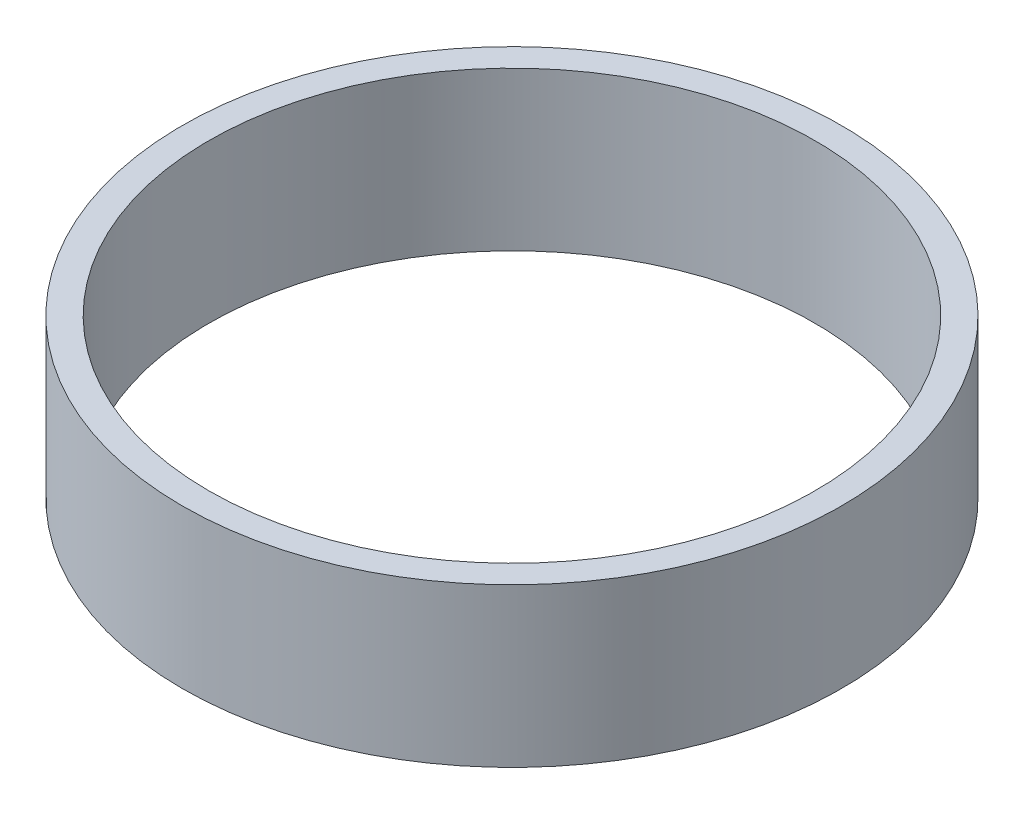
SolidWorks part; units mm, degrees
material "Silicon Rubber"
ref_plane "Front Plane" through (0, 0, 0) normal (0, 0, 1) x (1, 0, 0)
ref_plane "Top Plane" through (0, 0, 0) normal (0, 1, 0) x (1, 0, 0)
ref_plane "Right Plane" through (0, 0, 0) normal (1, 0, 0) x (0, 0, -1)
sketch "Sketch1" plane through (0, 0, 0) normal (0, 1, 0) x (1, 0, 0)
  circle A0 centre (0, 0) radius 5.75
  circle A1 centre (0, 0) radius 6.25
  dimension "D1" = 11.5
  dimension "D2" = 12.5
extrude "Boss-Extrude1" add sketch "Sketch1" along normal blind 3
